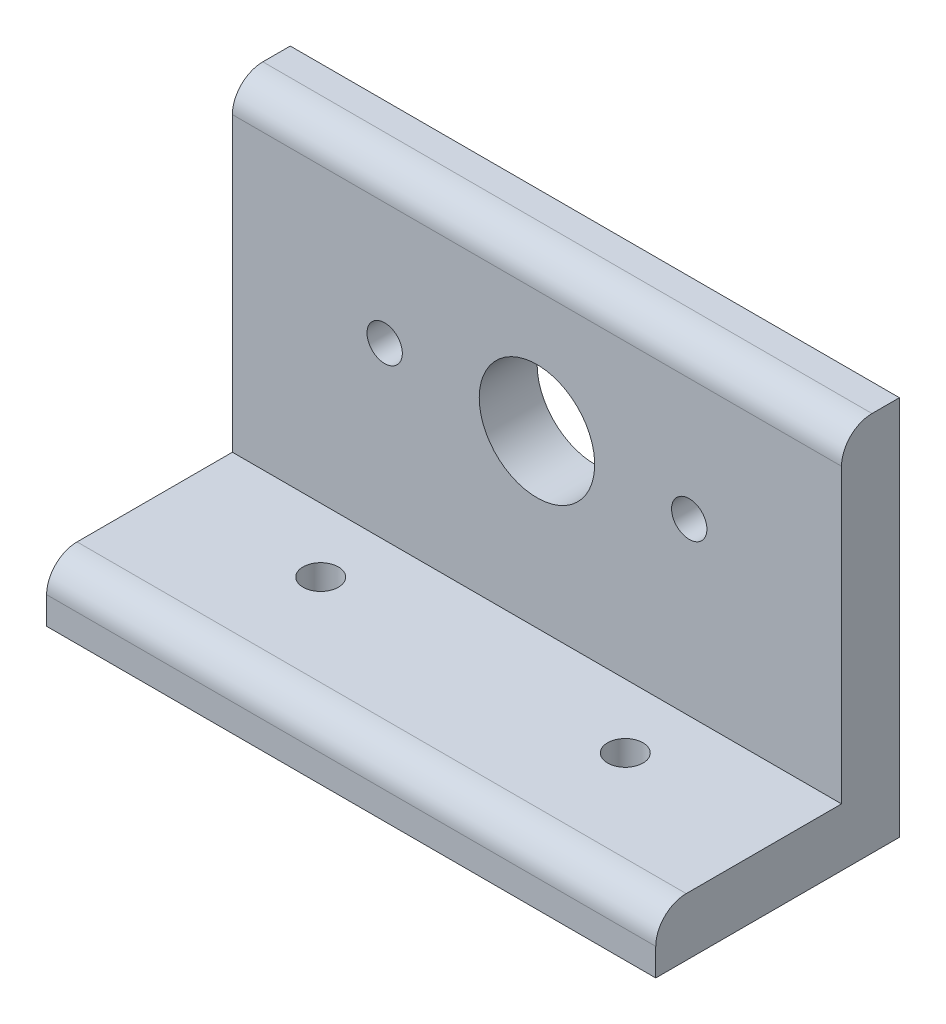
SolidWorks part; units mm, degrees
material "ABS"
ref_plane "Front Plane" through (0, 0, 0) normal (0, 0, 1) x (1, 0, 0)
ref_plane "Top Plane" through (0, 0, 0) normal (0, 1, 0) x (1, 0, 0)
ref_plane "Right Plane" through (0, 0, 0) normal (1, 0, 0) x (0, 0, -1)
sketch "Sketch1" plane through (0, 0, 0) normal (0, 1, 0) x (1, 0, 0)
  line L5 (0, 0) -> (50.8, 0)
  line L6 (0, 0) -> (0, 20.32)
  line L7 (0, 20.32) -> (50.8, 20.32)
  line L8 (50.8, 0) -> (50.8, 20.32)
  circle A0 centre (12.7, 10.16) radius 1.4732
  circle A1 centre (38.1, 10.16) radius 1.4732
  dimension "D3" = 2.9464
  dimension "D1" = 20.32
  dimension "D2" = 50.8
  dimension "D4" = 10.16
  dimension "D5" = 12.7
  dimension "D6" = 25.4
extrude "Boss-Extrude1" add sketch "Sketch1" along normal blind 4.826
sketch "Sketch2" plane through (0, 4.826, 0) normal (0, 1, 0) x (1, 0, 0)
  line L0 (50.8, 0) -> (50.8, 20.32) construction
  line L1 (0, 20.32) -> (50.8, 20.32)
  line L2 (0, 20.32) -> (0, 15.494)
  line L3 (0, 15.494) -> (50.8, 15.494)
  line L4 (50.8, 20.32) -> (50.8, 15.494)
  dimension "D1" = 4.826
extrude "Boss-Extrude2" add sketch "Sketch2" along normal blind 26.924
fillet "Fillet1" radius 2.54 2 edges at (25.4, 4.826, 0) (25.4, 31.75, -15.494)
sketch "Sketch3" plane through (0, 0, -20.32) normal (0, 0, -1) x (-1, 0, 0)
  line L0 (11.176, 0) -> (-11.176, 0) construction
  line L1 (-50.8, 31.75) -> (-50.8, 0) construction
  line L2 (-50.8, 31.75) -> (0, 31.75) construction
  circle A0 centre (-38.1, 19.05) radius 1.4732
  circle A1 centre (-12.7, 19.05) radius 1.4732
  circle A2 centre (-25.4, 19.05) radius 4.8133
  point P13 (-25.4, 31.75)
  dimension "D1" = 2.9464
  dimension "D5" = 9.6266
  dimension "D2" = 19.05
  dimension "D3" = 12.7
  dimension "D4" = 25.4
extrude "Cut-Extrude1" cut sketch "Sketch3" against normal blind 26.924
